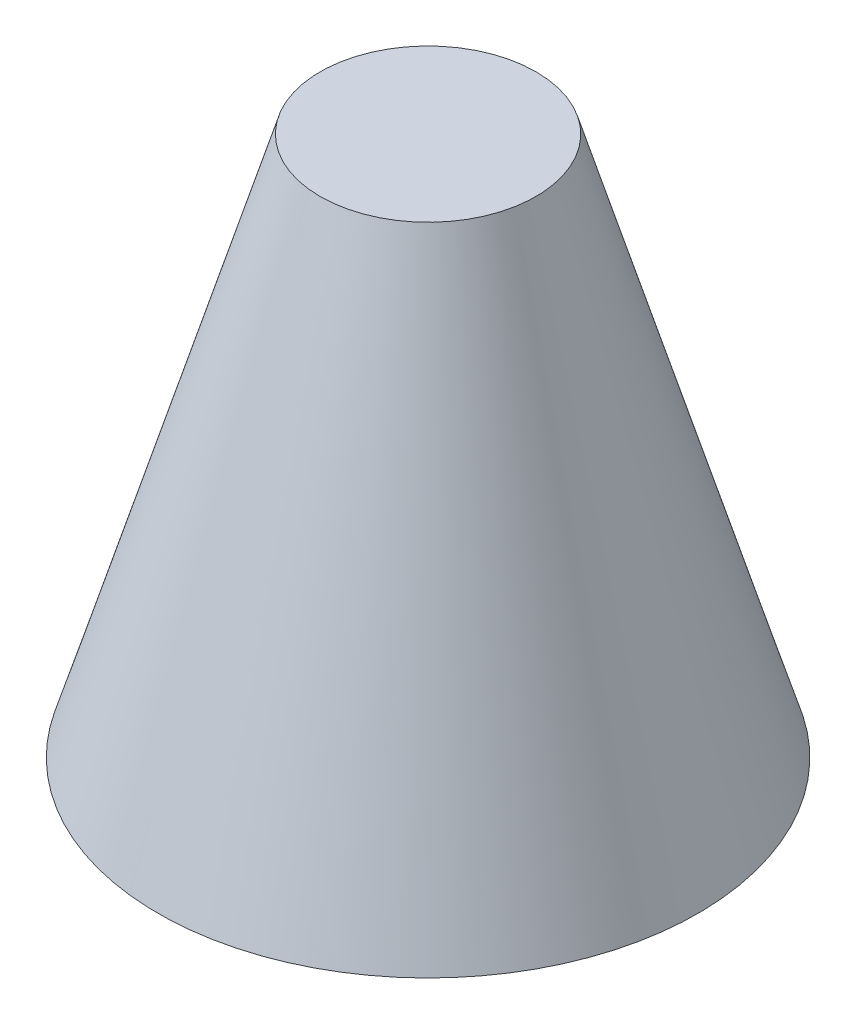
SolidWorks part; units mm, degrees
ref_plane "Alzado" through (0, 0, 0) normal (0, 0, 1) x (1, 0, 0)
ref_plane "Planta" through (0, 0, 0) normal (0, 1, 0) x (1, 0, 0)
ref_plane "Vista lateral" through (0, 0, 0) normal (1, 0, 0) x (0, 0, -1)
sketch "Croquis_perfil" plane through (0, 0, 0) normal (0, 0, 1) x (1, 0, 0)
  line L0 (0, 0) -> (0, 100) construction
  line L1 (0, 0) -> (50, 0)
  line L2 (50, 0) -> (20, 100)
  line L3 (20, 100) -> (0, 100)
  line L4 (0, 100) -> (0, 0)
  dimension "D1" = 20
  dimension "D2" = 50
  dimension "D3" = 100
revolve "Tronco_cono" add sketch "Croquis_perfil" angle 360 about L0
sketch "Croquis_agujeros_montaje" plane through (0, 0, 0) normal (0, 1, 0) x (1, 0, 0)
  circle A0 centre (0, 0) radius 4
  dimension "D1" = 8
extrude "Agujero_inserto_M6" cut sketch "Croquis_agujeros_montaje" along normal blind 14
